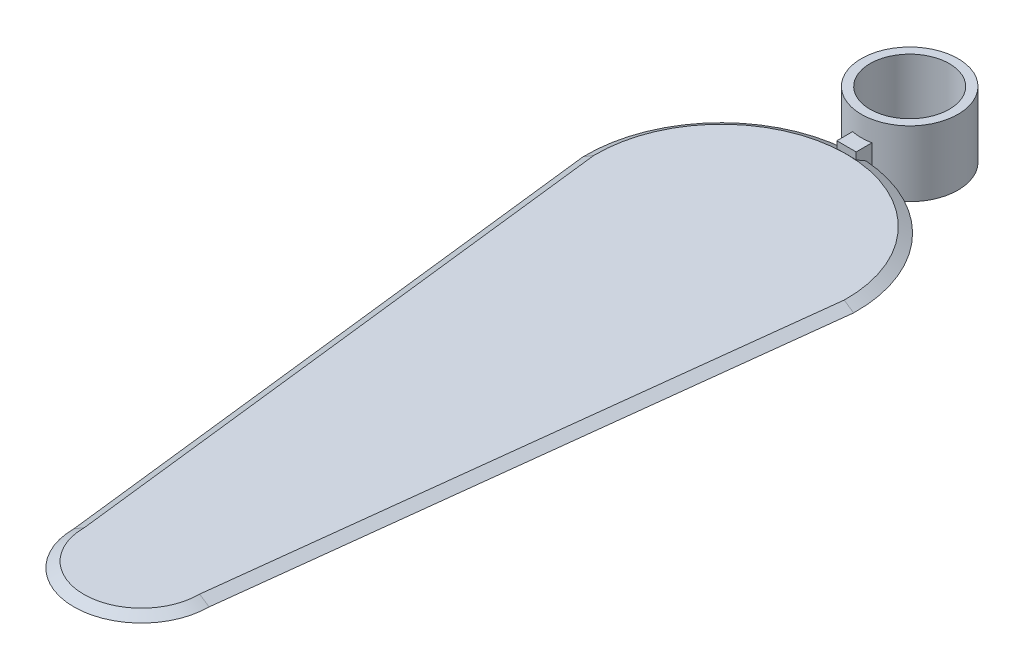
SolidWorks part; units mm, degrees
ref_plane "Alzado" through (0, 0, 0) normal (0, 0, 1) x (1, 0, 0)
ref_plane "Planta" through (0, 0, 0) normal (0, 1, 0) x (1, 0, 0)
ref_plane "Vista lateral" through (0, 0, 0) normal (1, 0, 0) x (0, 0, -1)
sketch "Croquis1" plane through (0, 0, 0) normal (0, 1, 0) x (1, 0, 0)
  line L0 (0, 0) -> (0, 30) construction
  line L3 (-3.5, 0) -> (-6.9984, 29.8482)
  line L4 (3.5, 0) -> (6.9984, 29.8482)
  arc A5 (6.9984, 29.8482) -> (-6.9984, 29.8482) centre (0, 30) ccw
  arc A6 (-3.5, 0) -> (3.5, 0) centre (0, 0) ccw
  point P3 (0, 7.6632)
  dimension "D1" = 7
  dimension "D2" = 7
  dimension "D3" = 30
extrude "Saliente-Extruir1" add sketch "Croquis1" along normal blind 0.3 draft 60
ref_plane "Plano1" through (0, 0, -37) normal (0, 0, 1) x (1, 0, 0)
sketch "Croquis3" plane through (0, 0, -37) normal (0, 0, 1) x (1, 0, 0)
  line L0 (0, 0) -> (0, 0.3) construction
  line L1 (2.9804, 0.3) -> (-2.9804, 0.3) construction
  line L3 (-0.5, -0.35) -> (0.5, -0.35)
  line L4 (-0.5, -0.35) -> (-0.5, 0.65)
  line L5 (-0.5, 0.65) -> (0.5, 0.65)
  line L6 (0.5, -0.35) -> (0.5, 0.65)
  line L7 (-0.5, -0.35) -> (0.5, 0.65) construction
  line L8 (-0.5, 0.65) -> (0.5, -0.35) construction
  point P8 (0, 0.15)
  dimension "D1" = 1
  dimension "D2" = 1
extrude "Saliente-Extruir2" add sketch "Croquis3" against normal blind 0.3 separate body
sketch "Croquis4" plane through (0, 0, -37) normal (0, 0, 1) x (1, 0, 0)
  line L1 (-0.5, 0.65) -> (0.5, 0.65)
  line L2 (-0.5, 0.65) -> (-0.5, -0.35)
  line L3 (-0.5, -0.35) -> (0.5, -0.35)
  line L4 (0.5, 0.65) -> (0.5, -0.35)
extrude "Saliente-Extruir3" add sketch "Croquis4" along normal up to vertex (0.5196 mm away)
sketch "Croquis5" plane through (0, 0, 0) normal (0, 1, 0) x (1, 0, 0)
  line L0 (0, 37.3) -> (0, 19.7808) construction
  line L1 (0.5, 37.3) -> (-0.5, 37.3) construction
  circle A0 centre (0, 39.7495) radius 2.5
  point P8 (0, 0)
  dimension "D1" = 5
extrude "Saliente-Extruir4" add sketch "Croquis5" along normal blind 1.7 and the other way blind 1.7
sketch "Croquis7" plane through (0, 1.7, 0) normal (0, 1, 0) x (1, 0, 0)
  circle A0 centre (0, 39.7495) radius 2.05
  dimension "D1" = 4.1
extrude "Cortar-Extruir1" cut sketch "Croquis7" against normal through all
